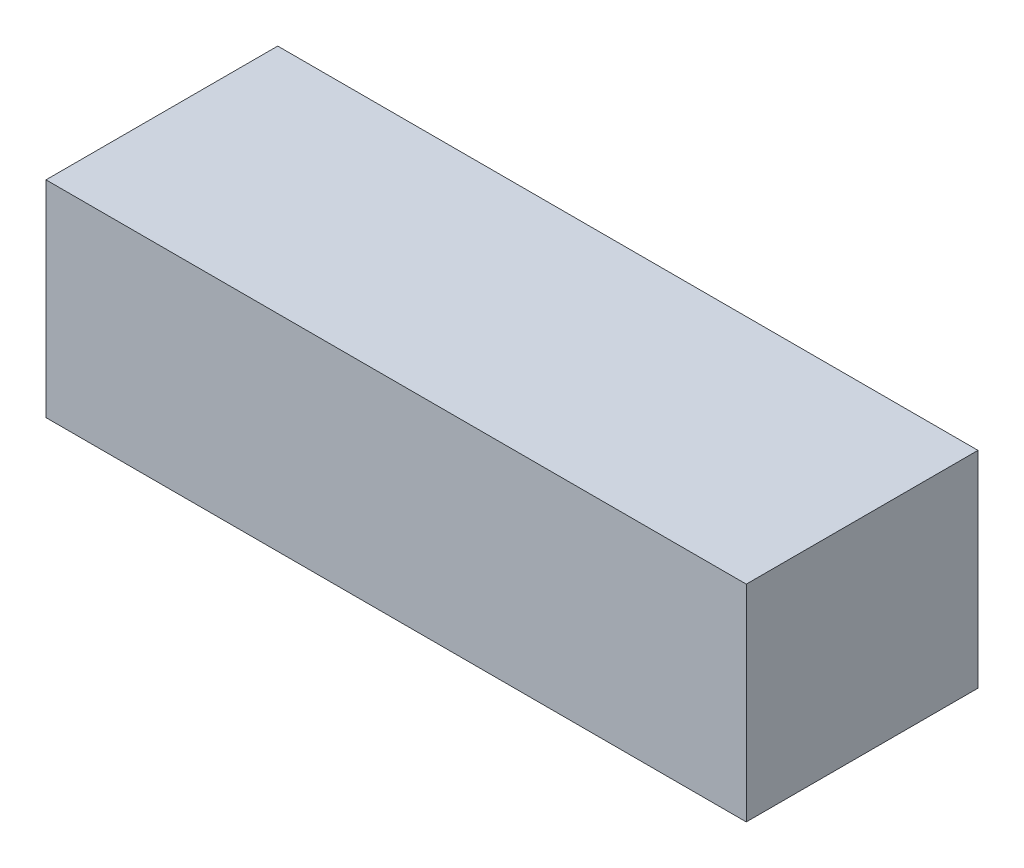
SolidWorks part; units mm, degrees
ref_plane "Front Plane" through (0, 0, 0) normal (0, 0, 1) x (1, 0, 0)
ref_plane "Top Plane" through (0, 0, 0) normal (0, 1, 0) x (1, 0, 0)
ref_plane "Right Plane" through (0, 0, 0) normal (1, 0, 0) x (0, 0, -1)
sketch "Sketch1" plane through (0, 0, 0) normal (0, 0, 1) x (1, 0, 0)
  line L0 (0, -55) -> (0, 55) construction
  line L1 (-68, 20) -> (68, 20)
  line L2 (-68, 20) -> (-68, -20)
  line L3 (-68, -20) -> (68, -20)
  line L4 (68, 20) -> (68, -20)
  line L5 (55, 0) -> (-55, 0) construction
  dimension "D1" = 136
  dimension "D2" = 40
  dimension "D3" = 68
  dimension "D4" = 20
extrude "Boss-Extrude1" add sketch "Sketch1" along normal blind 45
